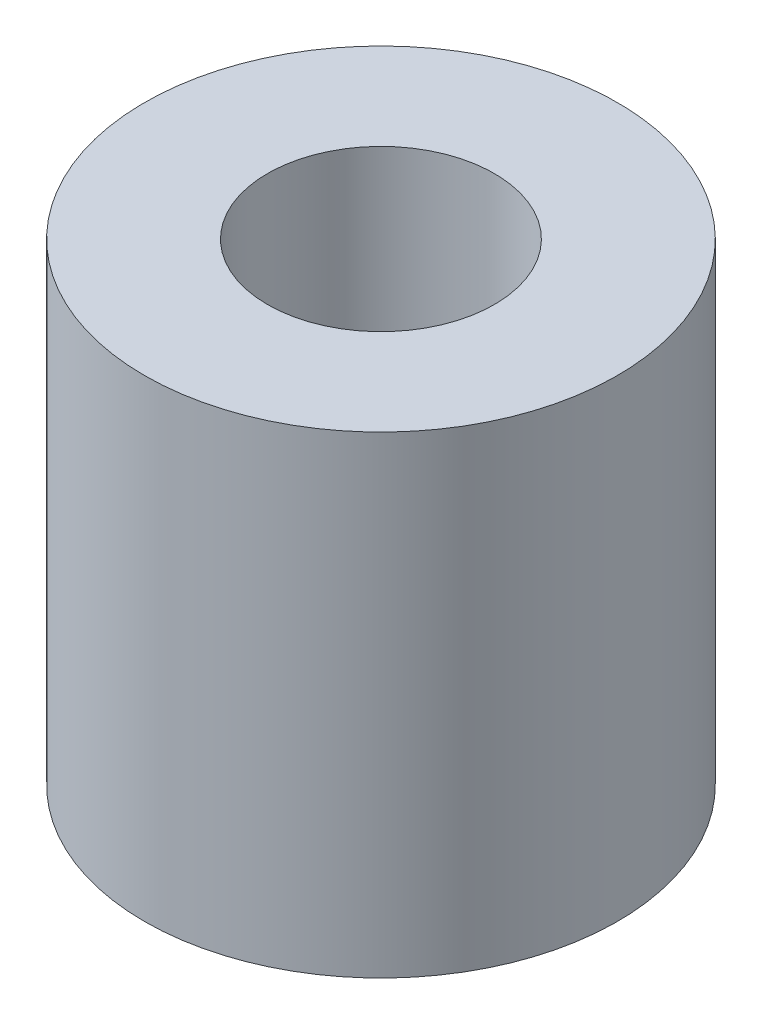
SolidWorks part; units mm, degrees
ref_plane "Front Plane" through (0, 0, 0) normal (0, 0, 1) x (1, 0, 0)
ref_plane "Top Plane" through (0, 0, 0) normal (0, 1, 0) x (1, 0, 0)
ref_plane "Right Plane" through (0, 0, 0) normal (1, 0, 0) x (0, 0, -1)
sketch "Sketch1" plane through (0, 0, 0) normal (0, 1, 0) x (1, 0, 0)
  circle A0 centre (0, 0) radius 1.524
  circle A1 centre (0, 0) radius 3.175
  dimension "D1" = 3.048
  dimension "D2" = 6.35
extrude "Boss-Extrude1" add sketch "Sketch1" along normal blind 6.35
